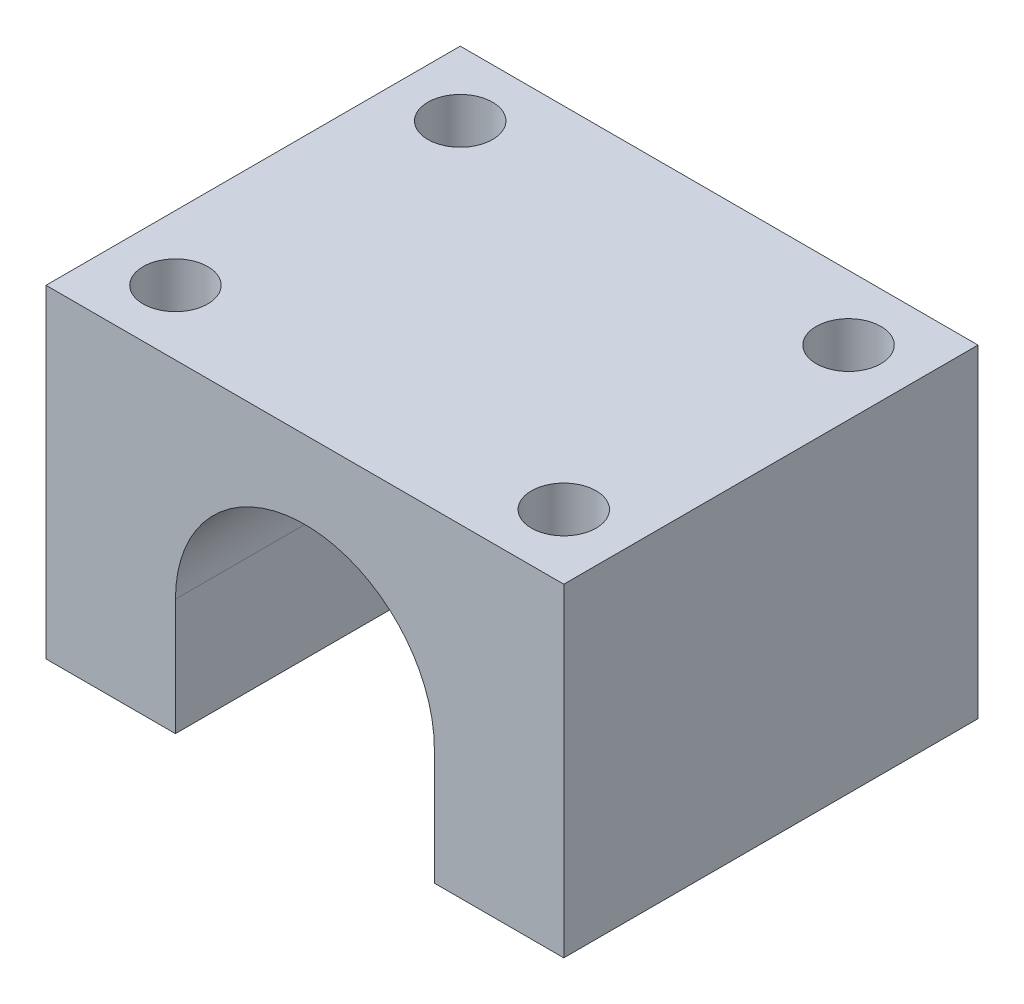
SolidWorks part; units mm, degrees
ref_plane "Front Plane" through (0, 0, 0) normal (0, 0, 1) x (1, 0, 0)
ref_plane "Top Plane" through (0, 0, 0) normal (0, 1, 0) x (1, 0, 0)
ref_plane "Right Plane" through (0, 0, 0) normal (1, 0, 0) x (0, 0, -1)
sketch "Sketch1" plane through (0, 0, 0) normal (0, 0, 1) x (1, 0, 0)
  line L0 (0, 0) -> (50.8, 0)
  line L1 (50.8, 0) -> (50.8, -31.75)
  line L2 (50.8, -31.75) -> (38.1, -31.75)
  line L3 (38.1, -31.75) -> (38.1, -20.32)
  line L4 (0, 0) -> (0, -31.75)
  line L5 (0, -31.75) -> (12.7, -31.75)
  line L6 (12.7, -31.75) -> (12.7, -20.32)
  arc A0 (38.1, -20.32) -> (12.7, -20.32) centre (25.4, -20.32) ccw
  dimension "D6" = 31.75
  dimension "D1" = 50.8
  dimension "D2" = 31.75
  dimension "D3" = 12.7
  dimension "D4" = 12.7
  dimension "D5" = 11.43
extrude "Boss-Extrude1" add sketch "Sketch1" along normal blind 40.64
sketch "Sketch2" plane through (0, 0, 0) normal (0, 1, 0) x (1, 0, 0)
  line L0 (50.8, 0) -> (0, 0) construction
  line L1 (0, -40.64) -> (0, 0) construction
  line L2 (0, -20.32) -> (50.8, -20.32) construction
  line L3 (50.8, -40.64) -> (50.8, 0) construction
  line L4 (25.4, 0) -> (25.4, -40.64) construction
  line L5 (50.8, -40.64) -> (0, -40.64) construction
  circle A0 centre (6.35, -6.35) radius 3.175
  circle A1 centre (44.45, -6.35) radius 3.175
  circle A2 centre (6.35, -34.29) radius 3.175
  circle A3 centre (44.45, -34.29) radius 3.175
  dimension "D1" = 6.35
  dimension "D2" = 6.35
  dimension "D3" = 6.35
extrude "Cut-Extrude1" cut sketch "Sketch2" against normal through all
